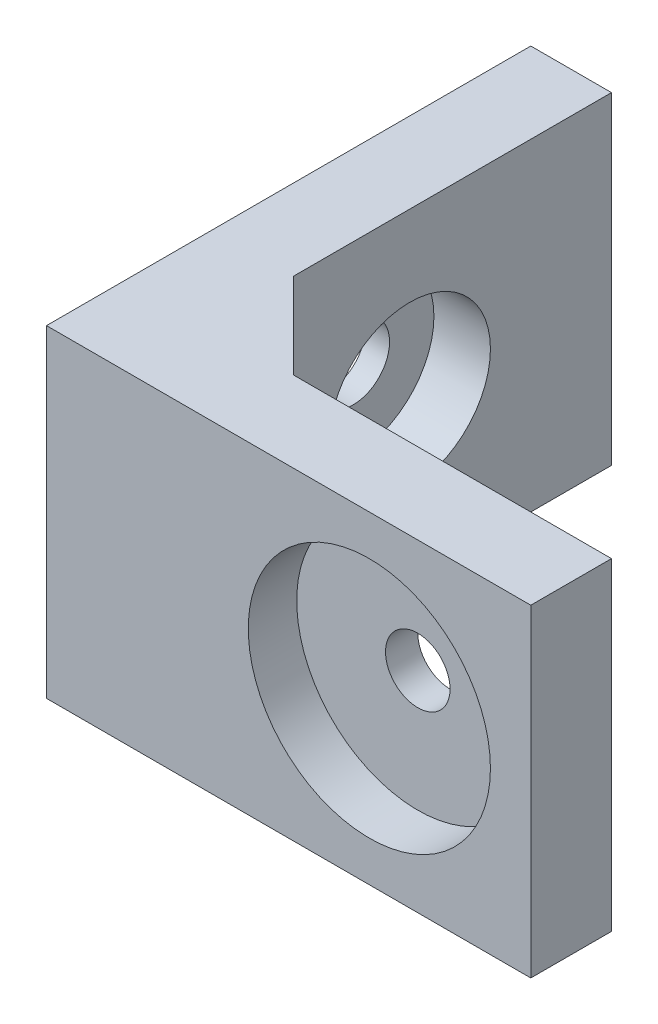
SolidWorks part; units mm, degrees
material "ABS"
ref_plane "Piano frontale" through (0, 0, 0) normal (0, 0, 1) x (1, 0, 0)
ref_plane "Piano superiore" through (0, 0, 0) normal (0, 1, 0) x (1, 0, 0)
ref_plane "Piano destro" through (0, 0, 0) normal (1, 0, 0) x (0, 0, -1)
sketch "Schizzo2" plane through (0, 0, 0) normal (0, 1, 0) x (1, 0, 0)
  line L0 (5, 30) -> (5, 10.3033)
  line L2 (10.3033, 5) -> (30, 5)
  line L3 (30, 5) -> (30, 0)
  line L4 (30, 0) -> (0, 0)
  line L5 (0, 0) -> (0, 30)
  line L6 (0, 30) -> (5, 30)
  line L7 (5, 10.3033) -> (10.3033, 5)
  dimension "D1" = 7.5
  dimension "D2" = 5
  dimension "D4" = 30
extrude "Estrusione-Estrusione2" add sketch "Schizzo2" along normal blind 20
sketch "Schizzo3" plane through (5, 0, 0) normal (1, 0, 0) x (0, 0, -1)
  line L0 (10.3033, 0) -> (30, 0) construction
  line L1 (30, 20) -> (30, 0) construction
  point P0 (17.5, 10)
  dimension "D1" = 10
  dimension "D2" = 12.5
hole_wizard "Foro lamato per Vite M4 a testa cilindrica piana-1" positions "Schizzo3" profile "Schizzo5" counterbore size "M4" standard "ISO"
sketch "Schizzo5" plane through (5, 10, -17.5) normal (0, 1, 0) x (0, 0, -1)
  line L0 (0, 0) -> (0, 16.3519)
  line L1 (0, 16.3519) -> (2.25, 15)
  line L2 (2.25, 15) -> (2.25, 3.5)
  line L3 (2.25, 3.5) -> (5, 3.5)
  line L4 (5, 3.5) -> (5, 0)
  line L5 (5, 0) -> (0, 0)
  line L10 (0, 16.3519) -> (-2.25, 15) construction
  line L11 (0, -6.35) -> (0, 107.95) construction
  dimension "Hole Dia." = 4.5
  dimension "Hole Depth" = 15
  dimension "C'Bore Dia." = 10
  dimension "C'Bore Depth" = 3.5
  dimension "Drill Angle" = 118
sketch "Schizzo6" plane through (0, 0, 0) normal (0, 0, 1) x (1, 0, 0)
  line L0 (0, 0) -> (30, 0) construction
  line L2 (30, 20) -> (30, 0) construction
  circle A0 centre (20, 10) radius 7.5
  dimension "D1" = 15
  dimension "D2" = 10
  dimension "D3" = 10
extrude "Taglio-Estrusione1" cut sketch "Schizzo6" against normal blind 3
hole_wizard "Foro per Vite M4-1" positions "Schizzo3D1" profile "Schizzo7" hole size "M4" standard "DIN"
sketch3d "Schizzo3D1"
  line L0 (20, 10, -3) -> (20, 10, 0) construction
  point P1 (20, 10, 0)
sketch "Schizzo7" plane through (20, 10, 0) normal (1, 0, 0) x (0, -1, 0)
  line L0 (0, 0) -> (0, 10.2017)
  line L1 (0, 10.2017) -> (2, 9)
  line L2 (2, 9) -> (2, 0)
  line L5 (2, 0) -> (0, 0)
  line L10 (0, 10.2017) -> (-2, 9) construction
  line L11 (0, -6.35) -> (0, 107.95) construction
  dimension "Hole Dia." = 4
  dimension "Hole Depth" = 9
  dimension "Drill Angle" = 118
